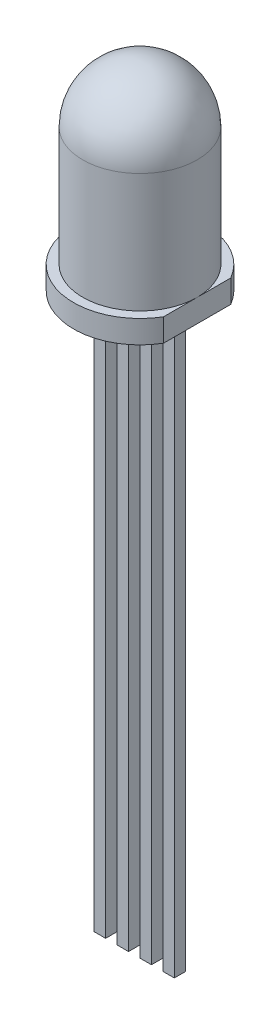
SolidWorks part; units mm, degrees
ref_plane "Front Plane" through (0, 0, 0) normal (0, 0, 1) x (1, 0, 0)
ref_plane "Top Plane" through (0, 0, 0) normal (0, 1, 0) x (1, 0, 0)
ref_plane "Right Plane" through (0, 0, 0) normal (1, 0, 0) x (0, 0, -1)
sketch "Sketch1" plane through (0, 0, 0) normal (0, 0, 1) x (1, 0, 0)
  line L0 (0, 0) -> (0, 19.6493) construction
  line L1 (0, 0) -> (2.9, 0)
  line L2 (2.5, 1) -> (2.5, 6.2)
  line L3 (2.5, 1) -> (2.9, 1)
  line L4 (2.9, 1) -> (2.9, 0)
  line L5 (0, 0) -> (0, 8.7)
  arc A0 (2.5, 6.2) -> (0, 8.7) centre (0, 6.2) ccw
  dimension "D1" = 5
  dimension "D2" = 1
  dimension "D3" = 8.7
  dimension "D4" = 5.8
revolve "Revolve1" add sketch "Sketch1" angle 360 about L0
sketch "Sketch2" plane through (0, 0, 0) normal (0, 1, 0) x (1, 0, 0)
  line L0 (0, 0) -> (3.2631, 0) construction
  line L1 (2.5, 0) -> (2.5, 2.5)
  line L2 (2.5, 2.5) -> (3.317, 2.5)
  line L3 (3.317, 2.5) -> (3.317, -2.186)
  line L4 (3.317, -2.186) -> (2.5, -2.186)
  line L5 (2.5, -2.186) -> (2.5, 0)
extrude "Cut-Extrude1" cut sketch "Sketch2" along normal through all both
sketch "Sketch3" plane through (0, 0, 0) normal (0, -1, 0) x (1, 0, 0)
  line L1 (-1.75, 0.25) -> (-1.25, 0.25)
  line L2 (-1.75, 0.25) -> (-1.75, -0.25)
  line L3 (-1.75, -0.25) -> (-1.25, -0.25)
  line L4 (-1.25, 0.25) -> (-1.25, -0.25)
  line L5 (-1.75, 0.25) -> (-1.25, -0.25) construction
  line L6 (-1.75, -0.25) -> (-1.25, 0.25) construction
  line L7 (-0.75, 0.25) -> (-0.25, 0.25)
  line L8 (-0.75, 0.25) -> (-0.75, -0.25)
  line L9 (-0.75, -0.25) -> (-0.25, -0.25)
  line L10 (-0.25, 0.25) -> (-0.25, -0.25)
  line L11 (-0.75, 0.25) -> (-0.25, -0.25) construction
  line L12 (-0.75, -0.25) -> (-0.25, 0.25) construction
  line L13 (0.25, 0.25) -> (0.75, 0.25)
  line L14 (0.25, 0.25) -> (0.25, -0.25)
  line L15 (0.25, -0.25) -> (0.75, -0.25)
  line L16 (0.75, 0.25) -> (0.75, -0.25)
  line L17 (0.25, 0.25) -> (0.75, -0.25) construction
  line L18 (0.25, -0.25) -> (0.75, 0.25) construction
  line L19 (1.25, 0.25) -> (1.75, 0.25)
  line L20 (1.25, 0.25) -> (1.25, -0.25)
  line L21 (1.25, -0.25) -> (1.75, -0.25)
  line L22 (1.75, 0.25) -> (1.75, -0.25)
  line L23 (1.25, 0.25) -> (1.75, -0.25) construction
  line L24 (1.25, -0.25) -> (1.75, 0.25) construction
  point P0 (-1.5, 0)
  point P5 (-0.5, 0)
  point P10 (0.5, 0)
  point P15 (1.5, 0)
  point P20 (0, 0)
  point P21 (1.7785, 0)
  point P22 (1.0182, 0)
  point P24 (-0.8679, 0)
  point P25 (2.2318, 0)
  point P26 (-0.5321, 0)
  dimension "D1" = 1
  dimension "D2" = 1
  dimension "D3" = 1
  dimension "D4" = 0.5
  dimension "D5" = 0.5
  dimension "D6" = 0.5
extrude "Boss-Extrude2" add sketch "Sketch3" along normal blind 25
